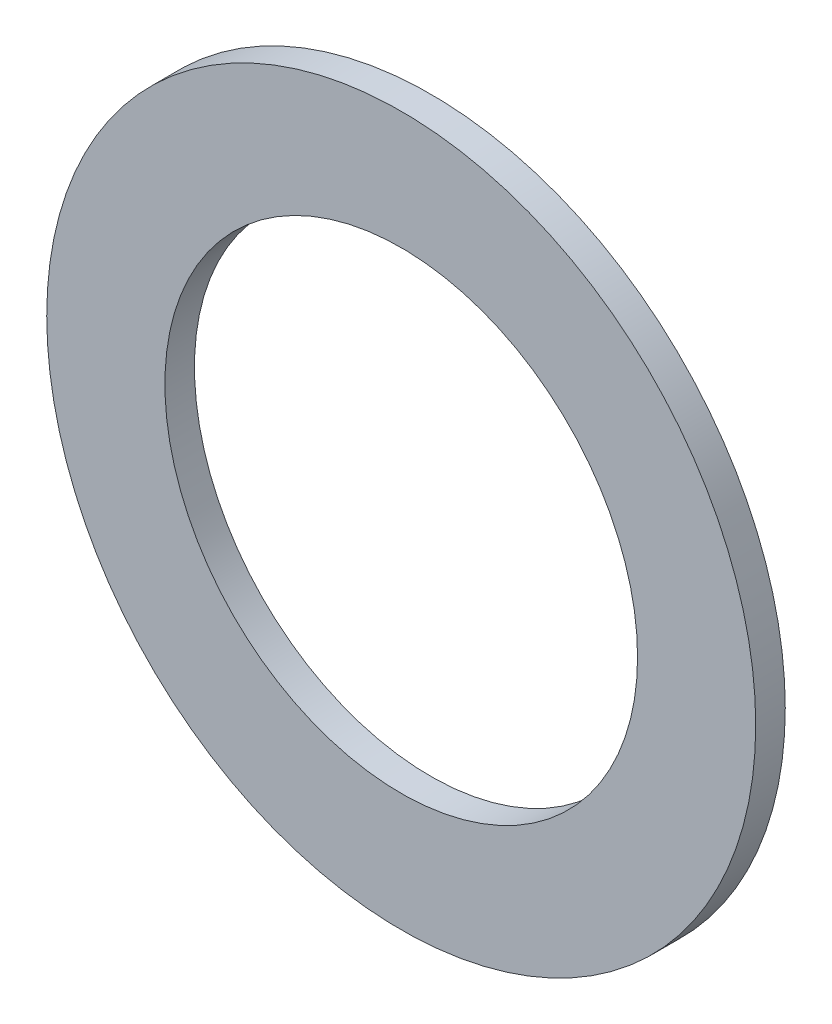
SolidWorks part; units mm, degrees
ref_plane "Front" through (0, 0, 0) normal (0, 0, 1) x (1, 0, 0)
ref_plane "Top" through (0, 0, 0) normal (0, 1, 0) x (1, 0, 0)
ref_plane "Right" through (0, 0, 0) normal (1, 0, 0) x (0, 0, -1)
sketch "Sketch1" plane through (0, 0, 0) normal (0, 0, 1) x (1, 0, 0)
  circle A0 centre (0, 0) radius 4
  circle A1 centre (0, 0) radius 6
  dimension "D1" = 8
  dimension "D2" = 12
extrude "Boss-Extrude1" add sketch "Sketch1" along normal blind 0.5
